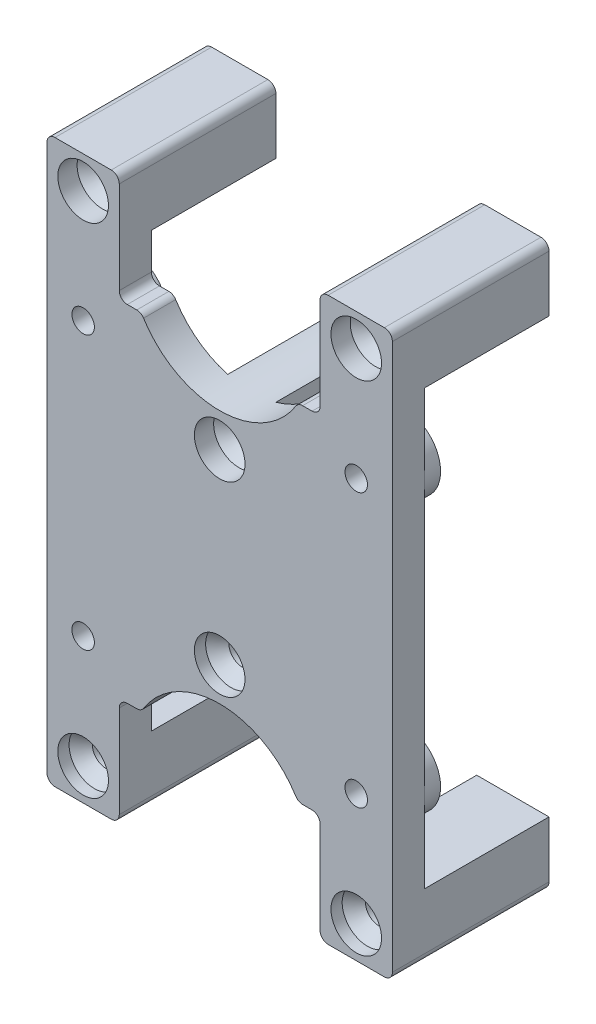
SolidWorks part; units mm, degrees
ref_plane "Front Plane" through (0, 0, 0) normal (0, 0, 1) x (1, 0, 0)
ref_plane "Top Plane" through (0, 0, 0) normal (0, 1, 0) x (1, 0, 0)
ref_plane "Right Plane" through (0, 0, 0) normal (1, 0, 0) x (0, 0, -1)
sketch "Layout" plane through (0, 0, 0) normal (0, 0, 1) x (1, 0, 0)
  line L16 (-17, 17) -> (17, 17) construction
  line L17 (17, 17) -> (17, -17) construction
  line L18 (17, -17) -> (-17, -17) construction
  line L19 (-17, -17) -> (-17, 17) construction
  line L20 (-21.5, -21.5) -> (-21.5, 21.5)
  line L21 (-21.5, 21.5) -> (21.5, 21.5)
  line L22 (21.5, 21.5) -> (21.5, -21.5)
  line L23 (21.5, -21.5) -> (-21.5, -21.5)
  point P6 (-17, 0)
  point P10 (17, 0)
  point P11 (0, 17)
  point P12 (0, -17)
  dimension "D1" = 34
  dimension "D2" = 34
  dimension "D3" = 34
  dimension "D4" = 4.5
sketch "Sketch2" plane through (0, 0, 0) normal (0, 0, 1) x (1, 0, 0)
  line L24 (-21.5, 35) -> (-21.5, -35)
  line L25 (-21.5, -35) -> (-12.5, -35)
  line L26 (-12.5, -35) -> (-12.5, -21.5)
  line L27 (21.5, -21.5) -> (-21.5, -21.5) construction
  line L28 (-12.5, -21.5) -> (12.5, -21.5)
  line L29 (12.5, -21.5) -> (12.5, -35)
  line L30 (12.5, -35) -> (21.5, -35)
  line L31 (21.5, -35) -> (21.5, 35)
  line L32 (21.5, 35) -> (12.5, 35)
  line L33 (12.5, 35) -> (12.5, 21.5)
  line L34 (-21.5, 21.5) -> (21.5, 21.5) construction
  line L35 (12.5, 21.5) -> (-12.5, 21.5)
  line L36 (-12.5, 21.5) -> (-12.5, 35)
  line L37 (-12.5, 35) -> (-21.5, 35)
  line L38 (-21.5, 35) -> (-17, 17) construction
  line L39 (-17, 17) -> (-12.5, 35) construction
  dimension "D1" = 70
extrude "Boss-Extrude1" add sketch "Sketch2" along normal blind 4
sketch "Sketch5" plane through (0, 0, 0) normal (0, 0, -1) x (-1, 0, 0)
  line L0 (21.5, -21.5) -> (21.5, 21.5) construction
  circle A9 centre (-17, 17) radius 4.5
  circle A10 centre (17, 17) radius 4.5
  circle A11 centre (17, -17) radius 4.5
  circle A12 centre (-17, -17) radius 4.5
extrude "Boss-Extrude2" add sketch "Sketch5" along normal blind 2
sketch "Sketch7" plane through (0, 0, 0) normal (0, 0, -1) x (-1, 0, 0)
  line L0 (-3, 21.5) -> (3, 21.5)
  line L2 (3, 21.5) -> (3, 7)
  line L3 (3, 7) -> (-3, 7)
  line L4 (-3, 7) -> (-3, 21.5)
  line L5 (10.725, 0) -> (-10.725, 0) construction
  line L6 (-3, -7) -> (-3, -21.5)
  line L7 (3, -7) -> (-3, -7)
  line L8 (3, -21.5) -> (3, -7)
  line L9 (-3, -21.5) -> (3, -21.5)
  line L10 (21.5, 21.5) -> (-21.5, 21.5) construction
  point P4 (0, 7)
  dimension "D1" = 14
  dimension "D2" = 6
extrude "Boss-Extrude3" add sketch "Sketch7" along normal up to surface (15.5 mm away)
sketch "Sketch13" plane through (0, 0, 0) normal (0, 0, -1) x (-1, 0, 0)
  line L11 (-21.5, 17) -> (-21.5, 35) construction
  line L20 (-12.5, 35) -> (-21.5, 35)
  line L21 (-12.5, 35) -> (-12.5, 27)
  line L22 (-12.5, 27) -> (-21.5, 27)
  line L23 (-21.5, 35) -> (-21.5, 27)
  line L24 (12.5, 21.5) -> (12.5, 35) construction
  line L25 (21.5, 35) -> (12.5, 35)
  line L26 (21.5, 35) -> (21.5, 27)
  line L27 (21.5, 27) -> (12.5, 27)
  line L28 (12.5, 35) -> (12.5, 27)
  line L29 (12.5, -35) -> (12.5, -21.5) construction
  line L30 (21.5, -35) -> (12.5, -35)
  line L31 (21.5, -35) -> (21.5, -27)
  line L32 (21.5, -27) -> (12.5, -27)
  line L33 (12.5, -35) -> (12.5, -27)
  line L34 (-21.5, -35) -> (-21.5, -17) construction
  line L35 (-12.5, -35) -> (-21.5, -35)
  line L36 (-12.5, -35) -> (-12.5, -27)
  line L37 (-12.5, -27) -> (-21.5, -27)
  line L38 (-21.5, -35) -> (-21.5, -27)
  dimension "D1" = 8
extrude "Boss-Extrude4" add sketch "Sketch13" along normal up to surface (15.5 mm away) up to face at (0, 14.25, -15.5)
sketch "Sketch6" plane through (0, 0, 4) normal (0, 0, 1) x (1, 0, 0)
  circle A0 centre (0, 27) radius 11.2
  circle A1 centre (0, 27) radius 11.2 construction
extrude "Cut-Extrude1" cut sketch "Sketch6" against normal through all
mirror "Mirror1" about plane through (0, 0, 0) normal (0, 1, 0) of "Cut-Extrude1"
sketch "Sketch3" plane through (0, 0, 4) normal (0, 0, 1) x (1, 0, 0)
  point P10 (-17, 17)
  point P13 (17, 17)
  point P16 (17, -17)
  point P19 (-17, -17)
hole_wizard "Ø2.8 (2.8) Diameter Hole1" positions "Sketch3" profile "Sketch4" hole size "Ø2.8" standard "ANSI Metric" end condition up to next
sketch "Sketch4" plane through (-17, 17, 4) normal (1, 0, 0) x (0, -1, 0)
  line L0 (0, 0) -> (0, 6)
  line L1 (0, 6) -> (1.4, 6)
  line L2 (1.4, 6) -> (1.4, 0)
  line L5 (1.4, 0) -> (0, 0)
  line L11 (0, -6.35) -> (0, 107.95) construction
  dimension "Thru Hole Dia." = 2.8
  dimension "Thru Hole Depth" = 6
sketch "Sketch8" plane through (0, 0, 4) normal (0, 0, -1) x (-1, 0, 0)
  line L0 (3, 7) -> (3, 16.2093) construction
  line L1 (-12.5, 27) -> (-12.5, 35) construction
  line L2 (-12.5, 35) -> (-21.5, 35) construction
  line L3 (21.5, 35) -> (12.5, 35) construction
  point P0 (0, 11.6046)
  point P3 (3, 11.6046)
  point P5 (-17, 31)
  point P7 (17, 31)
  point P13 (-12.5, 31)
  point P16 (-17, 35)
  point P19 (17, 35)
hole_wizard "CSK for M3 Flat Head Machine Screw1" positions "Sketch8" profile "Sketch9" countersink size "M3" standard "ANSI Metric" end condition through all
sketch "Sketch9" plane through (0, 11.6046, 4) normal (1, 0, 0) x (0, -1, 0)
  line L0 (0, 0) -> (0, 19.5)
  line L1 (0, 19.5) -> (1.7, 19.5)
  line L2 (1.7, 19.5) -> (1.7, 3.85)
  line L3 (1.7, 3.85) -> (3.15, 2.4)
  line L4 (3.15, 2.4) -> (3.15, 0)
  line L6 (3.15, 0) -> (0, 0)
  line L7 (-1.7, 3.85) -> (-3.15, 2.4) construction
  line L11 (0, -6.35) -> (0, 107.95) construction
  dimension "Thru Hole Dia." = 3.4
  dimension "Thru Hole Depth" = 19.5
  dimension "C'Sink Dia." = 6.3
  dimension "C'Sink Angle" = 90
  dimension "Head Clearance" = 2.4
sketch "Sketch10" plane through (0, 0, 4) normal (0, 0, 1) x (1, 0, 0)
  line L0 (0, 0) -> (21.5, 0) construction
  line L2 (21.5, 21.5) -> (21.5, -21.5) construction
  point P0 (0, -11.6046)
  point P13 (-17, -31)
  point P15 (17, -31)
hole_wizard "CSK for M3 Flat Head Machine Screw2" positions "Sketch10" profile "Sketch11" countersink size "M3" standard "ANSI Metric" end condition through all
sketch "Sketch11" plane through (0, -11.6046, 4) normal (1, 0, 0) x (0, -1, 0)
  line L0 (0, 0) -> (0, 19.5)
  line L1 (0, 19.5) -> (1.7, 19.5)
  line L2 (1.7, 19.5) -> (1.7, 2.85)
  line L3 (1.7, 2.85) -> (3.15, 1.4)
  line L4 (3.15, 1.4) -> (3.15, 0)
  line L6 (3.15, 0) -> (0, 0)
  line L7 (-1.7, 2.85) -> (-3.15, 1.4) construction
  line L11 (0, -6.35) -> (0, 107.95) construction
  dimension "Thru Hole Dia." = 3.4
  dimension "Thru Hole Depth" = 19.5
  dimension "C'Sink Dia." = 6.3
  dimension "C'Sink Angle" = 90
  dimension "Head Clearance" = 1.4
fillet "Fillet2" radius 1 20 edges at (3, 7, -7.75) (-3, 7, -7.75) (3, -7, -7.75) (-3, -7, -7.75) (-21.5, 35, -5.75) (-12.5, 35, -5.75) (12.5, 35, -5.75) (21.5, 35, -5.75) (12.5, -35, -5.75) (21.5, -35, -5.75) (-21.5, -35, -5.75) (-12.5, -35, -5.75) (-12.5, -21.5, 2) (9.7565, -21.5, 2) (-9.7565, -21.5, 2) (12.5, -21.5, 2) (-12.5, 21.5, 2) (-9.7565, 21.5, 2) (9.7565, 21.5, 2) (12.5, 21.5, 2)
